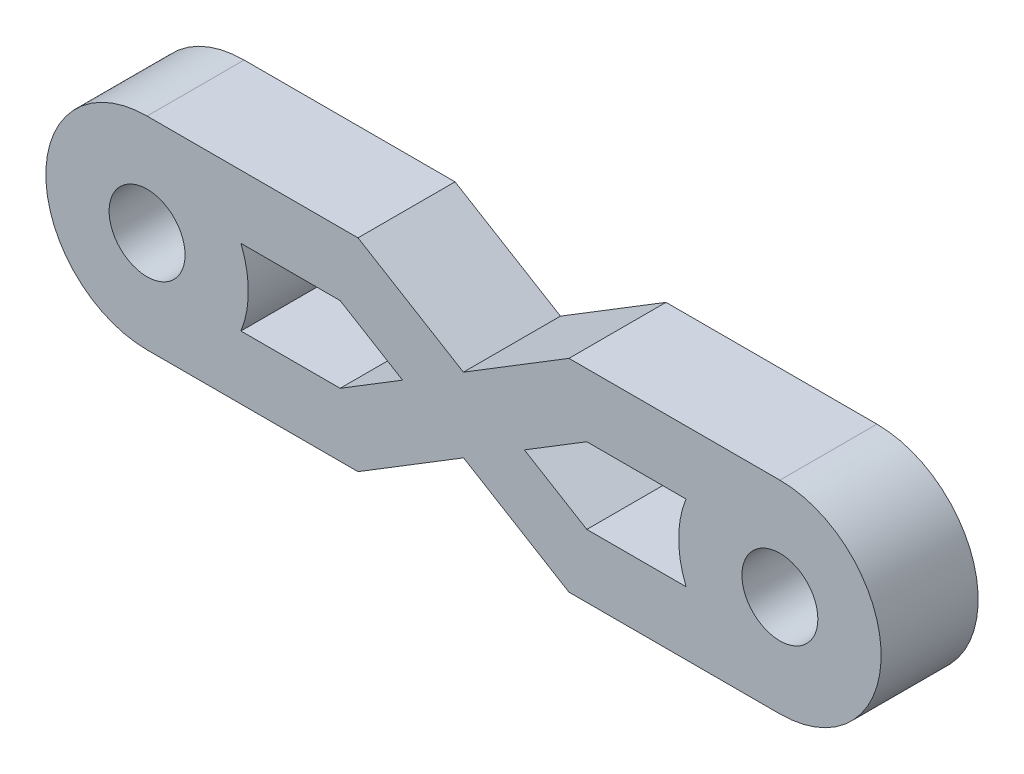
SolidWorks part; units mm, degrees
ref_plane "Front Plane" through (0, 0, 0) normal (0, 0, 1) x (1, 0, 0)
ref_plane "Top Plane" through (0, 0, 0) normal (0, 1, 0) x (1, 0, 0)
ref_plane "Right Plane" through (0, 0, 0) normal (1, 0, 0) x (0, 0, -1)
sketch "Sketch2" plane through (0, 0, 0) normal (0, 0, 1) x (1, 0, 0)
  line L0 (-117.2241, -4.8523) -> (-107.2241, -4.8523)
  line L1 (-87.2242, 4.8) -> (-97.2242, 4.8)
  line L2 (-97.2242, 4.8) -> (-102.2275, 1.7314)
  line L3 (-108.0708, -1.8523) -> (-112.7744, -1.8523)
  line L4 (-107.2241, -4.8523) -> (-102.2208, -1.7837)
  line L5 (-96.3775, 1.8) -> (-91.6739, 1.8)
  line L6 (-87.2242, -4.8) -> (-97.2242, -4.8)
  line L7 (-97.2242, -4.8) -> (-102.2208, -1.7837)
  line L8 (-108.0708, 1.7477) -> (-112.7744, 1.7477)
  line L9 (-117.2241, 4.7477) -> (-107.2241, 4.7477)
  line L10 (-107.2241, 4.7477) -> (-102.2275, 1.7314)
  line L11 (-96.3775, -1.8) -> (-91.6739, -1.8)
  line L12 (-99.3357, -0.0143) -> (-96.3775, 1.8)
  line L13 (-102.2208, -1.7837) -> (-99.3357, -0.0143) construction
  line L14 (-105.1126, -0.0381) -> (-108.0708, 1.7477)
  line L15 (-102.2208, -1.7837) -> (-105.1126, -0.0381) construction
  line L16 (-105.1126, -0.0381) -> (-108.0708, -1.8523)
  line L17 (-102.2275, 1.7314) -> (-105.1126, -0.0381) construction
  line L18 (-97.2242, -4.8) -> (-107.2241, -4.8523) construction
  line L19 (-99.3357, -0.0143) -> (-96.3775, -1.8)
  line L20 (-102.2275, 1.7314) -> (-99.3357, -0.0143) construction
  circle A0 centre (-117.2241, -0.0523) radius 1.8 construction
  circle A1 centre (-87.2242, 0) radius 1.8 construction
  circle A2 centre (-117.2241, -0.0523) radius 1.8
  circle A3 centre (-87.2242, 0) radius 1.8
  circle A4 centre (-117.2241, -0.0523) radius 4.8
  circle A5 centre (-87.2242, 0) radius 4.8
  circle M16 centre (-117.2241, -0.0523) radius 1.8
  circle M17 centre (-87.2242, 0) radius 1.8
  dimension "D1" = 3
  dimension "D2" = 3
  dimension "D3" = 3
  dimension "D4" = 3
extrude "Boss-Extrude1" add sketch "Sketch2" along normal up to surface (4.6 mm away) contours A4 M16 | A5 L1 L2 L10 L9 A4 L8 L14 L16 L3 L0 L4 L7 L6 L11 L19 L12 L5 | A5 M17
